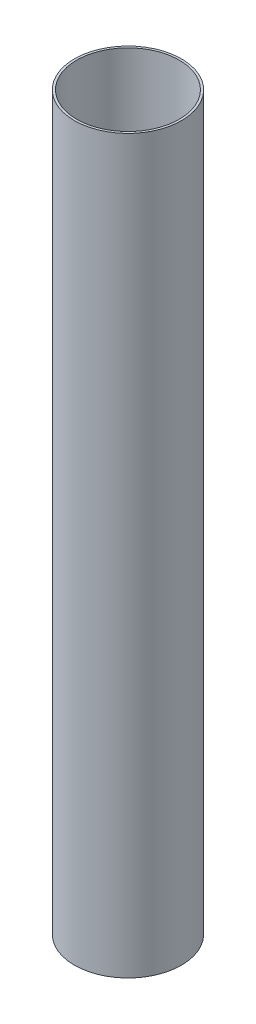
SolidWorks part; units mm, degrees
material "6061-T6 (SS)"
ref_plane "Front Plane" through (0, 0, 0) normal (0, 0, 1) x (1, 0, 0)
ref_plane "Top Plane" through (0, 0, 0) normal (0, 1, 0) x (1, 0, 0)
ref_plane "Right Plane" through (0, 0, 0) normal (1, 0, 0) x (0, 0, -1)
sketch "Sketch1" plane through (0, 0, 0) normal (0, 1, 0) x (1, 0, 0)
  circle A0 centre (0, 0) radius 76.2
  circle A1 centre (0, 0) radius 73.025
  dimension "D1" = 152.4
  dimension "D2" = 3.175
extrude "Boss-Extrude1" add sketch "Sketch1" along normal blind 1041.4
